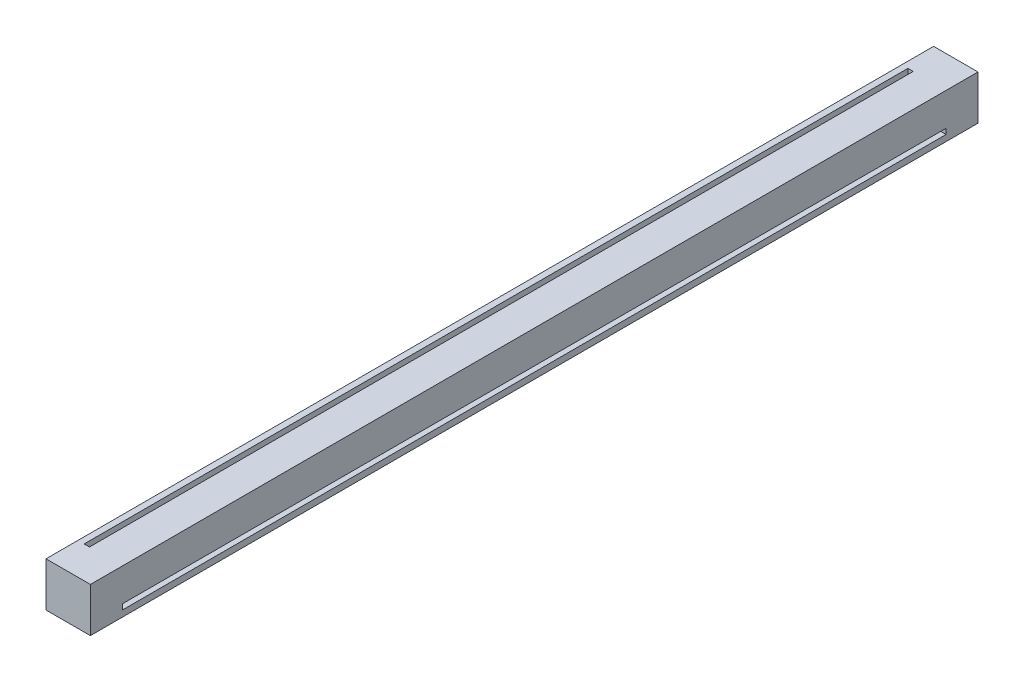
SolidWorks part; units mm, degrees
material "Buk"
ref_plane "Płaszczyzna przednia" through (0, 0, 0) normal (0, 0, 1) x (1, 0, 0)
ref_plane "Płaszczyzna górna" through (0, 0, 0) normal (0, 1, 0) x (1, 0, 0)
ref_plane "Płaszczyzna prawa" through (0, 0, 0) normal (1, 0, 0) x (0, 0, -1)
sketch "Szkic1" plane through (0, 0, 0) normal (0, 0, 1) x (1, 0, 0)
  line L1 (0, 0) -> (25, 0)
  line L2 (0, 0) -> (0, 25)
  line L3 (0, 25) -> (25, 25)
  line L4 (25, 0) -> (25, 25)
  dimension "D1" = 25
extrude "Dodanie-wyciągnięcie1" add sketch "Szkic1" along normal blind 500
sketch "Szkic2" plane through (0, 25, 0) normal (0, 1, 0) x (1, 0, 0)
  line L1 (6.5, -482) -> (3.5, -482)
  line L2 (6.5, -482) -> (6.5, -18)
  line L3 (6.5, -18) -> (3.5, -18)
  line L4 (3.5, -482) -> (3.5, -18)
  line L6 (0, -500) -> (0, 0) construction
  line L8 (25, 0) -> (0, 0) construction
  line L9 (25, -500) -> (0, -500) construction
  dimension "D1" = 3
  dimension "D2" = 3.5
  dimension "D3" = 18
  dimension "D4" = 18
extrude "Wytnij-wyciągnięcie1" cut sketch "Szkic2" against normal blind 3
sketch "Szkic3" plane through (25, 0, 0) normal (1, 0, 0) x (0, 0, -1)
  line L0 (-500, 0) -> (0, 0) construction
  line L1 (-482, 3.5) -> (-18, 3.5)
  line L2 (-482, 3.5) -> (-482, 6.5)
  line L3 (-482, 6.5) -> (-18, 6.5)
  line L4 (-18, 3.5) -> (-18, 6.5)
  line L5 (-500, 0) -> (-500, 25) construction
  line L6 (0, 0) -> (0, 25) construction
  dimension "D1" = 3.5
  dimension "D2" = 3
  dimension "D3" = 18
  dimension "D4" = 18
extrude "Wytnij-wyciągnięcie2" cut sketch "Szkic3" against normal blind 3
hole_wizard "Otwory ustalające Ø3.0mm1" positions "Szkic4" profile "Szkic5" hole size "Ø3.0" standard "Ansi Metric"
sketch "Szkic4" plane through (0, 0, 0) normal (0, 0, -1) x (-1, 0, 0)
  line L0 (0, 0) -> (-25, 0) construction
  line L2 (0, 25) -> (0, 0) construction
  point P0 (-14, 10)
  dimension "D1" = 10
  dimension "D2" = 14
sketch "Szkic5" plane through (14, 10, 0) normal (1, 0, 0) x (0, 1, 0)
  line L0 (0, 0) -> (0, 16.9013)
  line L1 (0, 16.9013) -> (1.5, 16)
  line L2 (1.5, 16) -> (1.5, 0)
  line L5 (1.5, 0) -> (0, 0)
  line L10 (0, 16.9013) -> (-1.5, 16) construction
  line L11 (0, -6.35) -> (0, 107.95) construction
  dimension "Œrednica otworu" = 3
  dimension "G³êbokoœæ otworu" = 16
  dimension "K¹t wiert³a" = 118
